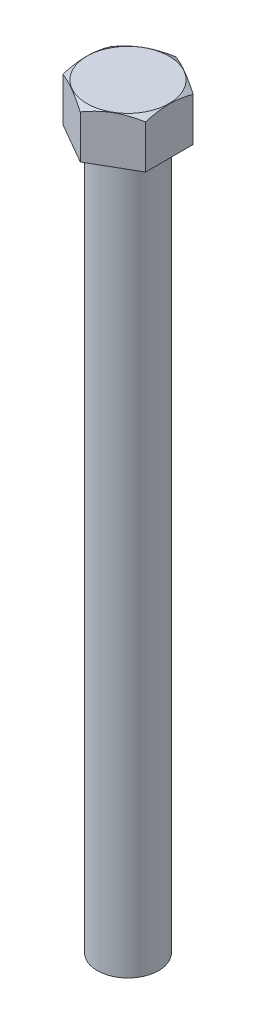
SolidWorks part; units mm, degrees
ref_plane "Front Plane" through (0, 0, 0) normal (0, 0, 1) x (1, 0, 0)
ref_plane "Top Plane" through (0, 0, 0) normal (0, 1, 0) x (1, 0, 0)
ref_plane "Right Plane" through (0, 0, 0) normal (1, 0, 0) x (0, 0, -1)
sketch "Sketch2" plane through (0, 0, 0) normal (0, 1, 0) x (1, 0, 0)
  line L1 (0, -0.2021) -> (0.175, -0.101)
  line L2 (0.175, -0.101) -> (0.175, 0.101)
  line L3 (0.175, 0.101) -> (0, 0.2021)
  line L4 (0, 0.2021) -> (-0.175, 0.101)
  line L5 (-0.175, 0.101) -> (-0.175, -0.101)
  line L6 (-0.175, -0.101) -> (0, -0.2021)
  circle A0 centre (0, 0) radius 0.175 construction
  point P1 (0, 0)
  dimension "D1" = 0.35
extrude "Boss-Extrude1" add sketch "Sketch2" along normal mid plane 0.2
sketch "Sketch3" plane through (0, 0.1, 0) normal (0, 1, 0) x (1, 0, 0)
  circle A0 centre (0, 0) radius 0.1739
extrude "Cut-Extrude1" cut sketch "Sketch3" against normal blind 0.2 draft 60 flip side to cut
sketch "Sketch4" plane through (0, -0.1, 0) normal (0, -1, 0) x (1, 0, 0)
  circle A0 centre (0, 0) radius 0.13
  dimension "D1" = 0.26
extrude "Boss-Extrude2" add sketch "Sketch4" along normal blind 3
